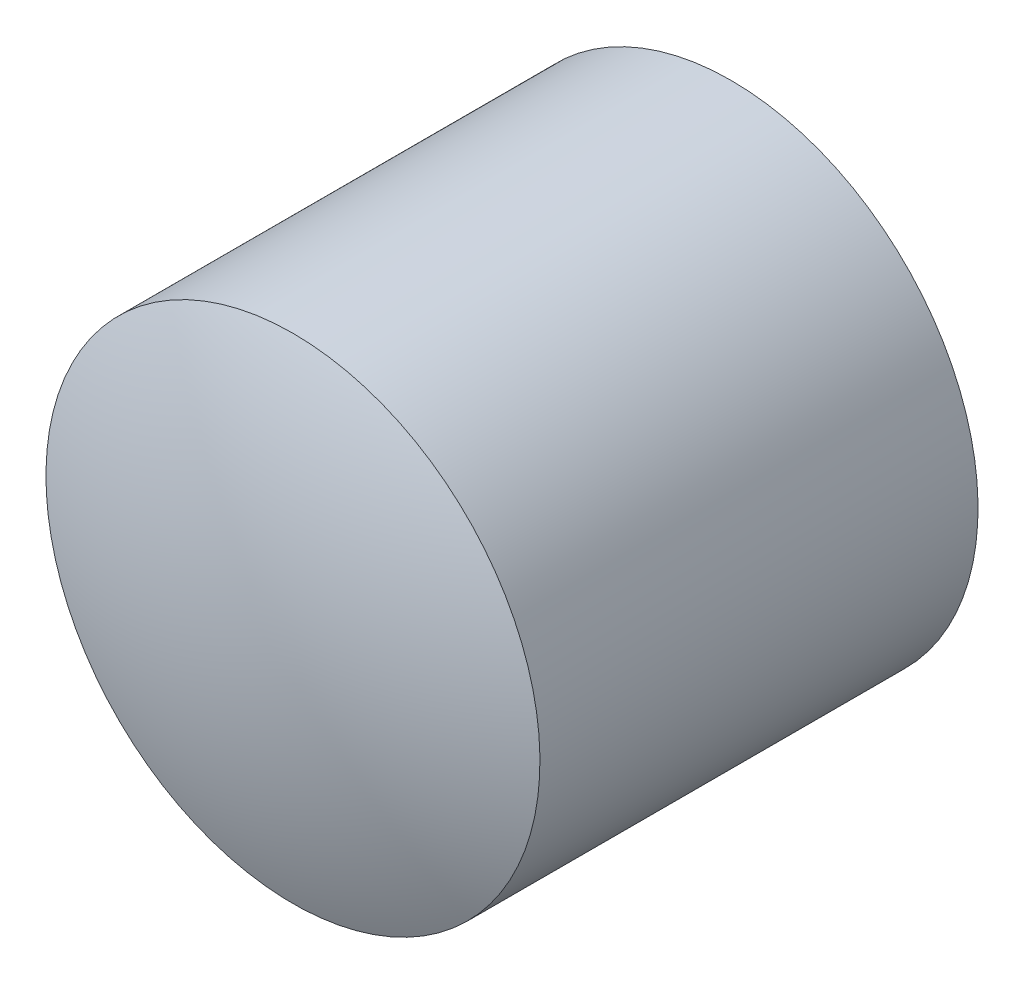
SolidWorks part; units mm, degrees
ref_plane "Front Plane" through (0, 0, 0) normal (0, 0, 1) x (1, 0, 0)
ref_plane "Top Plane" through (0, 0, 0) normal (0, 1, 0) x (1, 0, 0)
ref_plane "Right Plane" through (0, 0, 0) normal (1, 0, 0) x (0, 0, -1)
sketch "Sketch3" plane through (0, 0, 0) normal (1, 0, 0) x (0, 0, -1)
  line L3 (0, 0) -> (-6.8729, 0)
  line L4 (0, 0) -> (10, 0)
  line L5 (0, 0) -> (3.1271, 0)
  line L6 (10, 0) -> (10, 3.875)
  line L7 (10, 3.875) -> (-8.431, 3.875)
  arc A2 (0, 0) -> (0.7813, 3.875) centre (10, 0) cw
  arc A3 (-6.8729, 0) -> (-6.0915, 3.875) centre (3.1271, 0) cw
  dimension "D7" = 10
  dimension "D5" = 10
  dimension "D1" = 10
  dimension "D3" = 3.1271
  dimension "D6" = 3.875
revolve "Revolve1" add sketch "Sketch3" angle 360 about L3
equation "\"T_c\"= ( 1 + 1 / \"n\" ) * \"R_2\" - \"R_1\""
equation "\"R_1\"= \"gloabl_scale\" * 10mm"
equation "\"h\"= \"gloabl_scale\" * 7.75 / 2mm"
equation "\"gloabl_scale\"= 1"
equation "\"R_2\"= \"gloabl_scale\" * 10mm"
equation "\"x_origin_1\"= \"R_1\""
equation "\"x_origin_2\"= \"R_2\" - \"T_c\""
equation "\"T_edge\"= \"T_c\" - \"R_2\" * ( 1 - sqr ( 1 - \"h\" ^ 2 / \"R_2\" ^ 2 ) ) + 2mm"
equation "\"D1@Sketch3\"=\"R_1\""
equation "\"D3@Sketch3\"=\"R_2\"-\"T_c\""
equation "\"D7@Sketch3\"=\"R_2\""
equation "\"D5@Sketch3\"=\"R_1\""
equation "\"D6@Sketch3\"=\"h\""
equation "\"n\"= 1.455"
